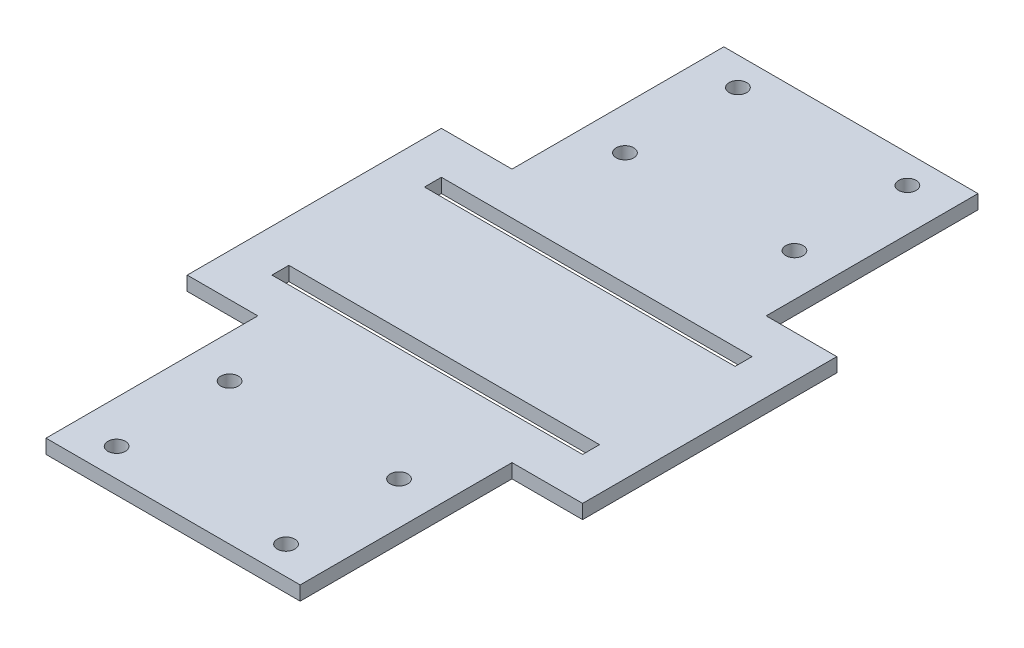
SolidWorks part; units mm, degrees
ref_plane "前视基准面" through (0, 0, 0) normal (0, 0, 1) x (1, 0, 0)
ref_plane "上视基准面" through (0, 0, 0) normal (0, 1, 0) x (1, 0, 0)
ref_plane "右视基准面" through (0, 0, 0) normal (1, 0, 0) x (0, 0, -1)
sketch "草图1" plane through (0, 0, 0) normal (0, 1, 0) x (1, 0, 0)
  line L0 (45, 45) -> (100, 45)
  line L1 (-45, 100) -> (45, 100)
  line L2 (-45, 100) -> (-45, 45)
  line L3 (-45, -100) -> (45, -100)
  line L4 (45, 100) -> (45, 45)
  line L5 (-45, 100) -> (45, -100) construction
  line L6 (-45, -100) -> (45, 100) construction
  line L7 (-100, 45) -> (-45, 45)
  line L8 (-100, 45) -> (-100, -45)
  line L9 (-100, -45) -> (-45, -45)
  line L10 (100, 45) -> (100, -45)
  line L11 (-100, 45) -> (100, -45) construction
  line L12 (-100, -45) -> (100, 45) construction
  line L13 (-45, -45) -> (-45, -100)
  line L14 (45, -45) -> (100, -45)
  line L15 (45, -45) -> (45, -100)
  point P0 (0, 0)
  point P5 (0, 0)
  dimension "D1" = 90
  dimension "D2" = 200
  dimension "D3" = 90
  dimension "D4" = 200
extrude "凸台-拉伸1" add sketch "草图1" along normal blind 5
sketch "草图3" plane through (0, 5, 0) normal (0, 1, 0) x (1, 0, 0)
  line L0 (-100, -45) -> (-45, -45) construction
  line L1 (-100, 45) -> (-70, 45)
  line L2 (-100, 45) -> (-100, -45)
  line L3 (-100, -45) -> (-70, -45)
  line L4 (-70, 45) -> (-70, -45)
  dimension "D1" = 30
extrude "切除-拉伸2" cut sketch "草图3" against normal blind 5
sketch "草图5" plane through (0, 5, 0) normal (0, 1, 0) x (1, 0, 0)
  line L0 (45, -45) -> (100, -45) construction
  line L1 (100, 45) -> (70, 45)
  line L2 (100, 45) -> (100, -45)
  line L3 (100, -45) -> (70, -45)
  line L4 (70, 45) -> (70, -45)
  dimension "D1" = 30
extrude "切除-拉伸3" cut sketch "草图5" against normal blind 5
ref_plane "基准面1" through (0, 5, 0) normal (0, 1, 0) x (1, 0, 0)
sketch "草图7" plane through (0, 5, 0) normal (0, 1, 0) x (1, 0, 0)
  line L1 (-45, 100) -> (45, 100)
  line L2 (-45, 100) -> (-45, 120)
  line L3 (-45, 120) -> (45, 120)
  line L4 (45, 100) -> (45, 120)
  dimension "D1" = 20
extrude "凸台-拉伸2" add sketch "草图7" against normal blind 5
sketch "草图9" plane through (0, 5, 0) normal (0, 1, 0) x (1, 0, 0)
  line L1 (45, -100) -> (-45, -100)
  line L2 (45, -100) -> (45, -120)
  line L3 (45, -120) -> (-45, -120)
  line L4 (-45, -100) -> (-45, -120)
  dimension "D1" = 20
extrude "凸台-拉伸3" add sketch "草图9" against normal blind 5
sketch "草图10" plane through (0, 5, 0) normal (0, 1, 0) x (1, 0, 0)
  line L0 (45, 120) -> (-45, 120) construction
  line L1 (-45, 120) -> (-45, 45) construction
  circle A0 centre (-30, 110) radius 3.1
  circle A1 centre (-30, 70) radius 3.1
  dimension "D1" = 6.2
  dimension "D2" = 10
  dimension "D3" = 15
  dimension "D4" = 2
extrude "切除-拉伸4" cut sketch "草图10" against normal blind 5
sketch "草图11" plane through (0, 5, 0) normal (0, 1, 0) x (1, 0, 0)
  line L0 (45, 45) -> (45, 120) construction
  line L1 (45, 120) -> (-45, 120) construction
  circle A0 centre (30, 110) radius 3.1
  circle A1 centre (30, 70) radius 3.1
  dimension "D1" = 6.2
  dimension "D2" = 15
  dimension "D3" = 10
  dimension "D4" = 2
extrude "切除-拉伸5" cut sketch "草图11" against normal blind 5
sketch "草图12" plane through (0, 5, 0) normal (0, 1, 0) x (1, 0, 0)
  line L0 (-45, -45) -> (-45, -120) construction
  line L1 (-45, -120) -> (45, -120) construction
  circle A0 centre (-30, -110) radius 3.1
  circle A1 centre (-30, -70) radius 3.1
  dimension "D1" = 6.2
  dimension "D2" = 15
  dimension "D3" = 10
  dimension "D4" = 2
extrude "切除-拉伸7" cut sketch "草图12" against normal blind 5
sketch "草图13" plane through (0, 5, 0) normal (0, 1, 0) x (1, 0, 0)
  line L0 (45, -120) -> (45, -45) construction
  line L1 (-45, -120) -> (45, -120) construction
  circle A0 centre (30, -110) radius 3.1
  circle A1 centre (30, -70) radius 3.1
  dimension "D1" = 6.2
  dimension "D2" = 15
  dimension "D3" = 10
  dimension "D4" = 2
extrude "切除-拉伸8" cut sketch "草图13" against normal blind 5
sketch "草图14" plane through (0, 5, 0) normal (0, 1, 0) x (1, 0, 0)
  line L0 (70, 45) -> (70, -45) construction
  line L1 (-50, 30) -> (50, 30)
  line L2 (-50, 30) -> (-50, 24)
  line L3 (-50, 24) -> (50, 24)
  line L4 (50, 30) -> (50, 24)
  line L5 (70, 45) -> (45, 45) construction
  dimension "D1" = 6
  dimension "D2" = 100
  dimension "D3" = 20
  dimension "D4" = 15
extrude "切除-拉伸9" cut sketch "草图14" against normal blind 5
sketch "草图15" plane through (0, 5, 0) normal (0, 1, 0) x (1, 0, 0)
  line L0 (-70, -45) -> (-70, 45) construction
  line L1 (-50, -24) -> (50, -24)
  line L2 (-50, -24) -> (-50, -30)
  line L3 (-50, -30) -> (50, -30)
  line L4 (50, -24) -> (50, -30)
  line L5 (-70, -45) -> (-45, -45) construction
  dimension "D1" = 6
  dimension "D2" = 100
  dimension "D3" = 20
  dimension "D4" = 15
extrude "切除-拉伸10" cut sketch "草图15" against normal blind 5
sketch "草图16" plane through (0, 5, 0) normal (0, 1, 0) x (1, 0, 0)
  line L1 (50, 24) -> (55, 24)
  line L2 (50, 24) -> (50, 30)
  line L3 (50, 30) -> (55, 30)
  line L4 (55, 24) -> (55, 30)
  dimension "D1" = 5
extrude "切除-拉伸11" cut sketch "草图16" against normal blind 5
sketch "草图17" plane through (0, 5, 0) normal (0, 1, 0) x (1, 0, 0)
  line L1 (50, -30) -> (55, -30)
  line L2 (50, -30) -> (50, -24)
  line L3 (50, -24) -> (55, -24)
  line L4 (55, -30) -> (55, -24)
  dimension "D1" = 6
  dimension "D2" = 5
extrude "切除-拉伸12" cut sketch "草图17" against normal blind 5
sketch "草图18" plane through (0, 5, 0) normal (0, 1, 0) x (1, 0, 0)
  line L1 (-50, 30) -> (-55, 30)
  line L2 (-50, 30) -> (-50, 24)
  line L3 (-50, 24) -> (-55, 24)
  line L4 (-55, 30) -> (-55, 24)
  dimension "D1" = 6
  dimension "D2" = 5
extrude "切除-拉伸13" cut sketch "草图18" against normal blind 5
sketch "草图19" plane through (0, 5, 0) normal (0, 1, 0) x (1, 0, 0)
  line L1 (-50, -30) -> (-55, -30)
  line L2 (-50, -30) -> (-50, -24)
  line L3 (-50, -24) -> (-55, -24)
  line L4 (-55, -30) -> (-55, -24)
  dimension "D1" = 6
  dimension "D2" = 5
extrude "切除-拉伸14" cut sketch "草图19" against normal blind 5
